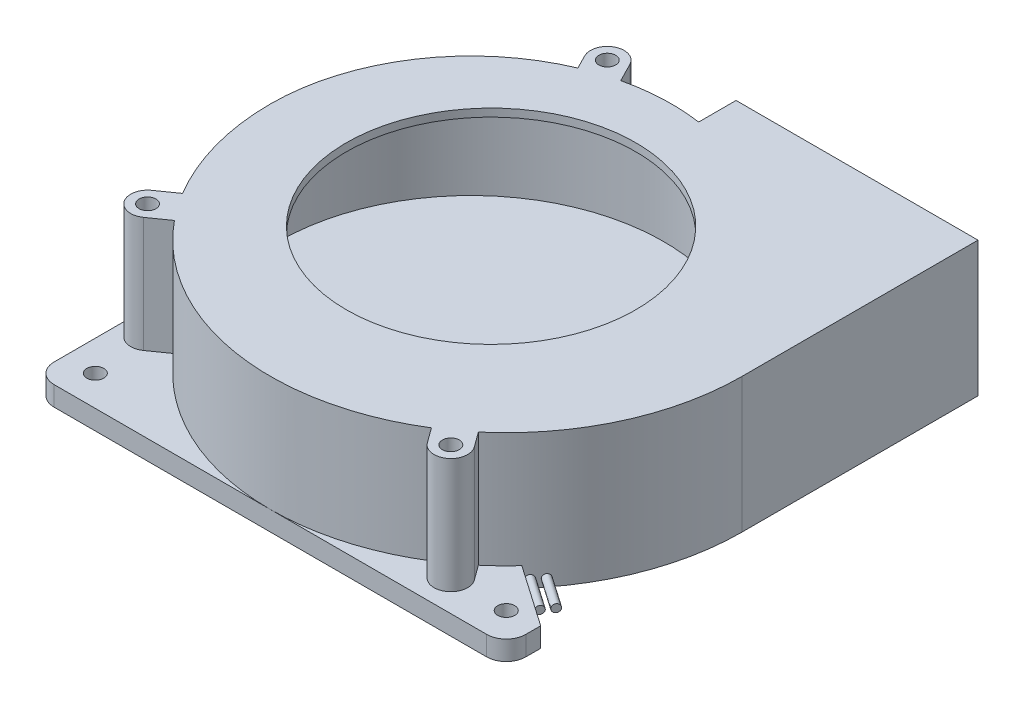
SolidWorks part; units mm, degrees
material "AISI 1020"
ref_plane "Frontal" through (0, 0, 0) normal (0, 0, 1) x (1, 0, 0)
ref_plane "Superior" through (0, 0, 0) normal (0, 1, 0) x (1, 0, 0)
ref_plane "Direito" through (0, 0, 0) normal (1, 0, 0) x (0, 0, -1)
sheet metal parameters "Chapa metálica2" thickness 6 parameters "D1"=1, "Espessura"=6
sketch "Esboço1" plane through (0, 0, 0) normal (0, 1, 0) x (1, 0, 0)
  line L1 (60.3, 60.3) -> (-60.3, 60.3)
  line L2 (60.3, 60.3) -> (60.3, -60.3)
  line L3 (60.3, -60.3) -> (-60.3, -60.3)
  line L4 (-60.3, 60.3) -> (-60.3, -60.3)
  line L5 (60.3, 60.3) -> (-60.3, -60.3) construction
  line L6 (60.3, -60.3) -> (-60.3, 60.3) construction
  point P0 (0, 0)
  dimension "D1" = 120.6
  dimension "D2" = 120.6
extrude "Ressalto-extrusão1" add sketch "Esboço1" along normal blind 5
sketch "Esboço2" plane through (0, 5, 0) normal (0, 1, 0) x (1, 0, 0)
  line L0 (60.3, -60.3) -> (60.3, 60.3) construction
  line L1 (-60.3, 60.3) -> (-60.3, -60.3) construction
  line L2 (60.3, 60.3) -> (-60.3, 60.3) construction
  line L3 (-1.55, 50.74) -> (-1.55, 60.3)
  line L4 (60.3, 0) -> (60.3, 60.3)
  line L5 (60.3, 60.3) -> (-1.55, 60.3)
  line L6 (-1.55, 60.3) -> (-1.4993, 60.4132)
  line L7 (-60.3, -60.3) -> (60.3, -60.3) construction
  line L8 (38.24, -52.4) -> (0, 0) construction
  line L9 (0, 0) -> (-53.89, -37.81) construction
  line L10 (-51.7037, -31.0293) -> (-56.3568, -34.2941)
  line L11 (-26.94, 52.77) -> (0, 0) construction
  line L12 (41.7094, -49.8681) -> (38.9254, -46.0533)
  line L13 (-30.7653, 50.8171) -> (-28.9464, 47.2542)
  line L14 (-46.77, -38.0612) -> (-51.4232, -41.3259)
  line L15 (34.7706, -54.9319) -> (31.9866, -51.117)
  line L16 (-23.1147, 54.7229) -> (-20.6744, 49.9429)
  line L17 (2.4668, -3.5159) -> (-51.4232, -41.3259) construction
  line L18 (34.7706, -54.9319) -> (-3.4694, -2.5319) construction
  line L19 (-2.4668, 3.5159) -> (-56.3568, -34.2941) construction
  line L20 (-30.7653, 50.8171) -> (-3.8253, -1.9529) construction
  line L22 (-23.1147, 54.7229) -> (3.8253, 1.9529) construction
  line L24 (41.7094, -49.8681) -> (3.4694, 2.5319) construction
  arc A0 (60.3, 0) -> (38.9254, -46.0533) centre (0, 0) cw
  arc A1 (-60.3, 0) -> (-28.9464, 47.2542) centre (-9.014, 0) cw
  circle A2 centre (-26.94, 52.77) radius 2.16
  circle A3 centre (-53.89, -37.81) radius 2.16
  circle A4 centre (38.24, -52.4) radius 2.16
  arc A5 (-56.3568, -34.2941) -> (-51.4232, -41.3259) centre (-53.89, -37.81) ccw
  arc A6 (34.7706, -54.9319) -> (41.7094, -49.8681) centre (38.24, -52.4) ccw
  arc A7 (-23.1147, 54.7229) -> (-30.7653, 50.8171) centre (-26.94, 52.77) ccw
  arc A8 (-51.7037, -31.0293) -> (-60.3, 0) centre (0, 0) cw
  arc A9 (-20.6744, 49.9429) -> (-1.55, 50.74) centre (-9.014, 0) cw
  arc A10 (31.9866, -51.117) -> (-46.77, -38.0612) centre (0, 0) cw
  circle A11 centre (-5.0117, 1.136) radius 37
  line M8 (60.3, -60.3) -> (60.3, 60.3)
  line M9 (60.3, 60.3) -> (-60.3, 60.3)
  dimension "D4" = 4.32
  dimension "D8" = 19.9
  dimension "D10" = 8.59
  dimension "D11" = 74
  dimension "D12" = 13.15
  dimension "D1" = 9.56
  dimension "D2" = 61.85
  dimension "D3" = 5.37
  dimension "D5" = 31.2
  dimension "D6" = 20.33
  dimension "D7" = 4.25
  dimension "D9" = 5.74
  dimension "D13" = 18.3
extrude "Ressalto-extrusão2" add sketch "Esboço2" along normal blind 29.48 contours A10 L15 A6 L12 A0 L3 A9 L16 A7 L13 A1 A8 L10 A5 L14 A11 A4 A3 A2 M8 M9
sketch "Esboço3" plane through (0, 5, 0) normal (0, 1, 0) x (1, 0, 0)
  line L9 (58.3, 60.3) -> (0.45, 60.3)
  line L10 (60.3, 60.3) -> (-1.55, 60.3) construction
  line L18 (32.4868, -48.4097) -> (36.3862, -53.7529)
  line L19 (40.0938, -51.0471) -> (36.1945, -45.7039)
  line L20 (58.3, 0) -> (58.3, 58.3)
  line L21 (58.3, 58.3) -> (0.45, 58.3)
  line L22 (0.45, 58.3) -> (0.45, 48.3689)
  line L23 (-21.7324, 47.6168) -> (-24.896, 53.8135)
  line L24 (-28.984, 51.7265) -> (-26.1654, 46.2054)
  line L25 (-49.0061, -31.5799) -> (-55.2081, -35.9313)
  line L26 (-52.5719, -39.6887) -> (-46.3699, -35.3373)
  line L29 (58.3, 0) -> (58.3, 60.3)
  line L31 (0.45, 60.3) -> (0.45, 48.3689)
  arc A16 (-46.3699, -35.3373) -> (32.4868, -48.4097) centre (0, 0) ccw
  arc A17 (36.3862, -53.7529) -> (40.0938, -51.0471) centre (38.24, -52.4) ccw
  arc A18 (36.1945, -45.7039) -> (58.3, 0) centre (0, 0) ccw
  arc A19 (0.45, 48.3689) -> (-21.7324, 47.6168) centre (-9.014, 0) ccw
  arc A20 (-24.896, 53.8135) -> (-28.984, 51.7265) centre (-26.94, 52.77) ccw
  arc A21 (-26.1654, 46.2054) -> (-58.3, 0) centre (-9.014, 0) ccw
  arc A22 (-58.3, 0) -> (-49.0061, -31.5799) centre (0, 0) ccw
  arc A23 (-55.2081, -35.9313) -> (-52.5719, -39.6887) centre (-53.89, -37.81) ccw
  arc A24 (-46.3699, -35.3373) -> (36.1945, -45.7039) centre (0, 0) ccw
  arc A26 (36.1945, -45.7039) -> (58.3, 0) centre (0, 0) ccw
  arc A27 (0.45, 48.3689) -> (-21.7324, 47.6168) centre (-9.014, 0) ccw
  arc A29 (-21.7324, 47.6168) -> (-58.3, 0) centre (-9.014, 0) ccw
  arc A30 (-58.3, 0) -> (-46.3699, -35.3373) centre (0, 0) ccw
  dimension "D1" = 2
extrude "Corte-extrusão1" cut sketch "Esboço3" along normal offset from surface (27.48 mm away) 2 up to face at (-5.0117, 34.48, 35.864)
sketch "Esboço4" plane through (0, 5, 0) normal (0, 1, 0) x (1, 0, 0)
  line L1 (0, 26.884) -> (0, -26.884) construction
  line L2 (-23.341, 0) -> (23.341, 0) construction
  circle A0 centre (-52.525, 52.525) radius 2.175
  circle A1 centre (-52.525, -52.525) radius 2.175
  circle A2 centre (52.525, -52.525) radius 2.175
  dimension "D1" = 100.7
  dimension "D2" = 100.7
  dimension "D3" = 4.35
extrude "Corte-extrusão2" cut sketch "Esboço4" against normal up to next
sketch "Esboço5" plane through (0, 5, 0) normal (0, 1, 0) x (1, 0, 0)
  line L0 (60.3, -51.5) -> (44.584, -40.6)
  line L1 (60.3, -60.3) -> (60.3, 0) construction
  line L2 (0, -60.3) -> (60.3, -60.3) construction
  line L3 (60.3, 0) -> (60.3, -51.5)
  arc A0 (38.9254, -46.0533) -> (60.3, 0) centre (0, 0) ccw construction
  arc A1 (38.9254, -46.0533) -> (60.3, 0) centre (0, 0) ccw
  line M5 (60.3, -60.3) -> (60.3, 0)
  arc M6 (60.3, 0) -> (38.9254, -46.0533) centre (0, 0) cw
  dimension "D1" = 8.8
  dimension "D2" = 19.7
extrude "Corte-extrusão3" cut sketch "Esboço5" against normal up to next contours L0 M5 M6
fillet "Filete1" radius 5 3 edges at (60.3, 2.5, 60.3) (-60.3, 2.5, 60.3) (-60.3, 2.5, -60.3)
ref_plane "Plano1" through (49.1163, 0, 34.0651) normal (-0.8217, 0, -0.5699) x (0, 1, 0)
sketch "Esboço6" plane through (49.1163, 0, 34.0651) normal (-0.8217, 0, -0.5699) x (0, 1, 0)
  line L0 (1.9759, -6.4528) -> (1.9759, -3.4528) construction
  line L1 (0, 34.3653) -> (0, -7.9528) construction
  circle A0 centre (1.9759, -6.4528) radius 1
  circle A1 centre (1.9759, -3.4528) radius 1
  dimension "D1" = 2
  dimension "D2" = 2
  dimension "D3" = 1.9759
  dimension "D4" = 1.5
  dimension "D5" = 3
extrude "Ressalto-extrusão3" add sketch "Esboço6" against normal blind 10
flat pattern "Padrão-Plano2"
sketch "Curva-Linhas2" plane through (0, 0, 0) normal (0, 1, 0) x (-1, 0, 0)
